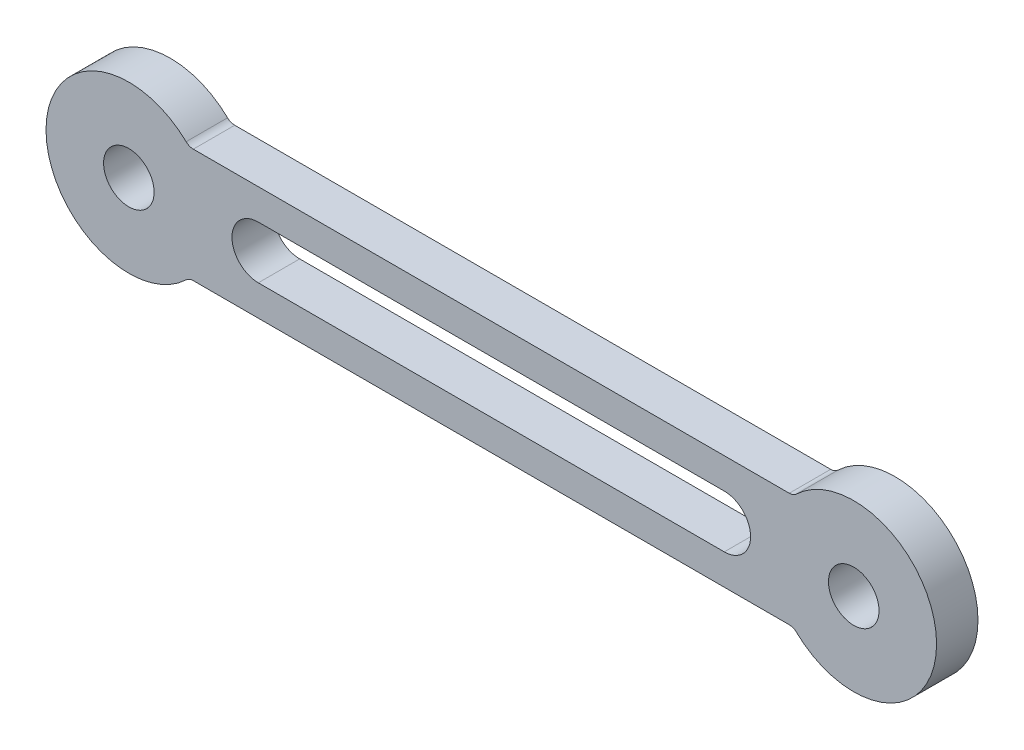
SolidWorks part; units mm, degrees
ref_plane "前视基准面" through (0, 0, 0) normal (0, 0, 1) x (1, 0, 0)
ref_plane "上视基准面" through (0, 0, 0) normal (0, 1, 0) x (1, 0, 0)
ref_plane "右视基准面" through (0, 0, 0) normal (1, 0, 0) x (0, 0, -1)
sketch "草图1" plane through (0, 0, 0) normal (0, 0, 1) x (1, 0, 0)
  line L0 (-35, 0) -> (35, 0) construction
  line L1 (-29.1905, 5.5) -> (29.1905, 5.5)
  line L2 (-29.1905, -5.5) -> (29.1905, -5.5)
  line L3 (-22.5, 0) -> (22.5, 0)
  line L4 (-22.5, 0) -> (22.5, 0) construction
  line L5 (-22.5, 2.5407) -> (22.5, 2.5407)
  line L6 (-22.5, -2.5407) -> (22.5, -2.5407)
  arc A0 (-29.1905, 5.5) -> (-29.1905, -5.5) centre (-35, 0) ccw
  arc A1 (29.1905, -5.5) -> (29.1905, 5.5) centre (35, 0) ccw
  circle A2 centre (-35, 0) radius 2.44
  circle A3 centre (35, 0) radius 2.44
  arc A4 (-22.5, 2.5407) -> (-22.5, -2.5407) centre (-22.5, 0) ccw
  arc A5 (22.5, -2.5407) -> (22.5, 2.5407) centre (22.5, 0) ccw
  point P3 (0, 0)
  point P10 (0, 0)
  point P13 (0, 0)
  dimension "D2" = 16
  dimension "D3" = 16
  dimension "D5" = 4.88
  dimension "D6" = 4.88
  dimension "D1" = 70
  dimension "D4" = 11
extrude "凸台-拉伸1" add sketch "草图1" along normal blind 4 contours L2 A1 L1 A0 A5 L6 A4 L5 A3 A2
fillet "圆角2" radius 1 1 edges at (-29.1905, 5.5, 2)
fillet "圆角4" radius 1 1 edges at (-29.1905, -5.5, 2)
fillet "圆角5" radius 1 1 edges at (29.1905, 5.5, 2)
fillet "圆角6" radius 1 1 edges at (29.1905, -5.5, 2)
